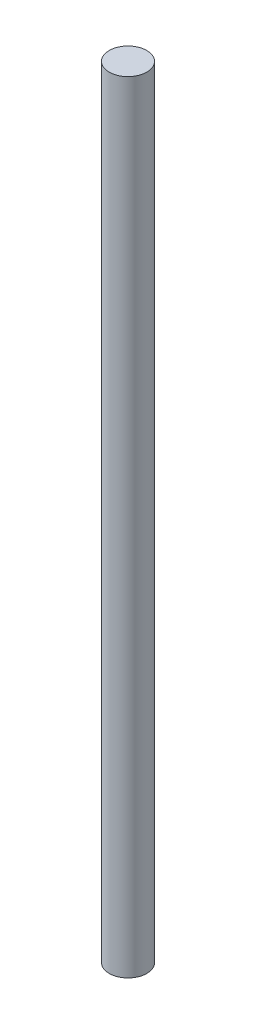
SolidWorks part; units mm, degrees
ref_plane "Płaszczyzna przednia" through (0, 0, 0) normal (0, 0, 1) x (1, 0, 0)
ref_plane "Płaszczyzna górna" through (0, 0, 0) normal (0, 1, 0) x (1, 0, 0)
ref_plane "Płaszczyzna prawa" through (0, 0, 0) normal (1, 0, 0) x (0, 0, -1)
sketch "Szkic1" plane through (0, 0, 0) normal (0, 1, 0) x (1, 0, 0)
  circle A0 centre (0, 0) radius 2.5
  dimension "D1" = 5
extrude "Dodanie-wyciągnięcie1" add sketch "Szkic1" along normal blind 104
